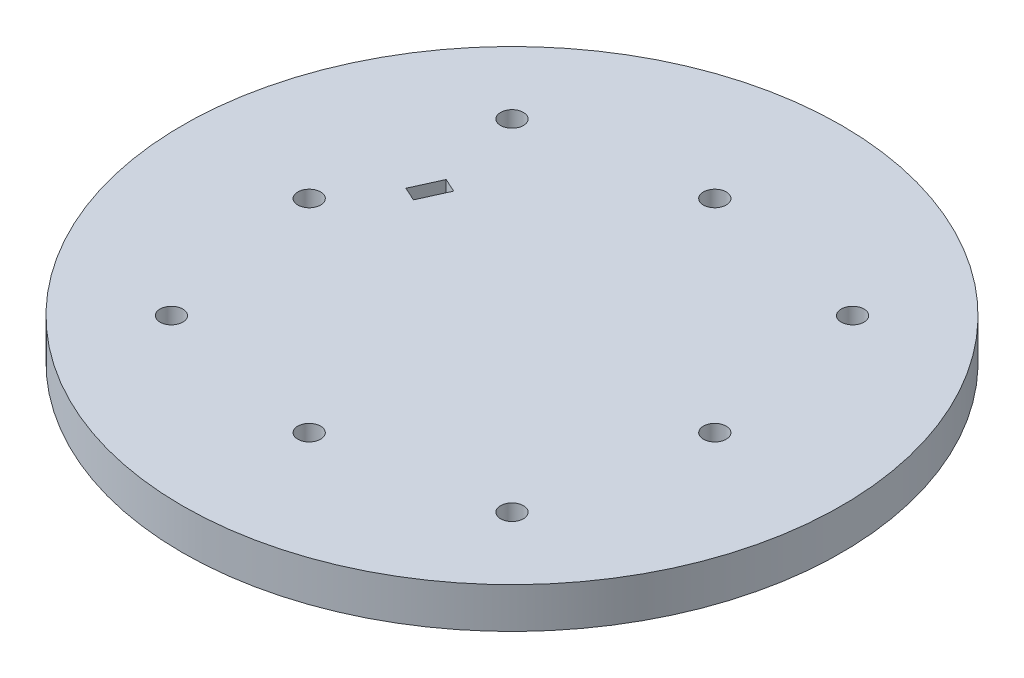
SolidWorks part; units mm, degrees
material "6061-T6 (SS)"
ref_plane "Front Plane" through (0, 0, 0) normal (0, 0, 1) x (1, 0, 0)
ref_plane "Top Plane" through (0, 0, 0) normal (0, 1, 0) x (1, 0, 0)
ref_plane "Right Plane" through (0, 0, 0) normal (1, 0, 0) x (0, 0, -1)
sketch "Sketch2" plane through (0, 0, 0) normal (0, 1, 0) x (1, 0, 0)
  circle A0 centre (0, 0) radius 65
  dimension "D1" = 130
extrude "Boss-Extrude1" add sketch "Sketch2" along normal blind 8
sketch "Sketch3" plane through (0, 0, 0) normal (0, -1, 0) x (1, 0, 0)
  circle A0 centre (0, 0) radius 21
  dimension "D1" = 42
extrude "Cut-Extrude1" cut sketch "Sketch3" against normal blind 4.5
sketch "Sketch4" plane through (0, 8, 0) normal (0, 1, 0) x (1, 0, 0)
  circle A0 centre (0, 0) radius 40 construction
  circle A1 centre (-40, 0) radius 2.25
  circle A2 centre (0, 40) radius 2.25
  circle A3 centre (0, 0) radius 40 construction
  circle A4 centre (40, 0) radius 2.25
  circle A5 centre (0, 0) radius 40 construction
  circle A6 centre (0, -40) radius 2.25
  circle A7 centre (0, 0) radius 40 construction
  point P17 (0, 0)
  dimension "D1" = 80
  dimension "D2" = 4.5
  dimension "D3" = 4
extrude "Cut-Extrude2" cut sketch "Sketch4" against normal through all
sketch "Sketch5" plane through (0, 8, 0) normal (0, 1, 0) x (1, 0, 0)
  line L0 (0, 40) -> (-40, 0) construction
  line L1 (-20, 20) -> (-33.5876, 33.5876) construction
  line L2 (-33.5876, 33.5876) -> (33.5876, -33.5876) construction
  line L3 (0, 0) -> (-33.5876, -33.5876) construction
  line L4 (-33.5876, -33.5876) -> (33.5876, 33.5876) construction
  circle A0 centre (0, 0) radius 47.5 construction
  circle A1 centre (-33.5876, 33.5876) radius 2.25
  circle A2 centre (33.5876, 33.5876) radius 2.25
  circle A3 centre (0, 0) radius 47.5 construction
  circle A4 centre (33.5876, -33.5876) radius 2.25
  circle A5 centre (0, 0) radius 47.5 construction
  circle A6 centre (-33.5876, -33.5876) radius 2.25
  circle A7 centre (0, 0) radius 47.5 construction
  point P25 (0, 0)
  dimension "D2" = 4.5
  dimension "D3" = 4
  dimension "D1" = 95
extrude "Cut-Extrude3" cut sketch "Sketch5" against normal through all
sketch "Sketch6" plane through (0, 0, 0) normal (0, -1, 0) x (1, 0, 0)
  line L0 (0, 0) -> (-68.3319, -30.9152) construction
  line L1 (-29.4805, -10.045) -> (-27.0073, -15.5116)
  line L6 (-27.0073, -15.5116) -> (-16.0741, -10.5651)
  line L7 (-16.0741, -10.5651) -> (-18.5474, -5.0986)
  line L8 (-18.5474, -5.0986) -> (-29.4805, -10.045)
  line L9 (-20.3695, -5.923) -> (-17.8963, -11.3895) construction
  circle A1 centre (0, 0) radius 21 construction
  point P9 (-17.3108, -7.8318)
  dimension "D1" = 6
  dimension "D2" = 4
  dimension "D3" = 10
extrude "path_trench" cut sketch "Sketch6" against normal blind 2
sketch "Sketch7" plane through (0, 0, 0) normal (0, -1, 0) x (1, 0, 0)
  line L5 (-29.4805, -10.045) -> (-32.2137, -11.2816)
  line L6 (-32.2137, -11.2816) -> (-29.7405, -16.7482)
  line L7 (-29.7405, -16.7482) -> (-27.0073, -15.5116)
  line L8 (-27.0073, -15.5116) -> (-17.7001, -11.3007) construction
  line L9 (-20.1733, -5.8342) -> (-29.4805, -10.045) construction
  line L10 (-29.4805, -10.045) -> (-27.0073, -15.5116)
  dimension "D1" = 3
sketch "CDG" plane through (0, 0, 0) normal (0, -1, 0) x (1, 0, 0)
  circle A0 centre (0, 0) radius 27 construction
  circle A1 centre (-27, 0) radius 1.7
  circle A2 centre (13.5, 23.3827) radius 1.7
  circle A3 centre (0, 0) radius 27 construction
  circle A4 centre (13.5, -23.3827) radius 1.7
  circle A5 centre (0, 0) radius 27 construction
  point P14 (0, 0)
  dimension "D1" = 54
  dimension "D3" = 3.4
  dimension "D2" = 3
extrude "CDG_CUT" cut sketch "CDG" against normal blind 6
extrude "Cut-Extrude4" cut sketch "Sketch7" against normal through all
sketch "Sketch8" plane through (0, 8, 0) normal (0, 1, 0) x (1, 0, 0)
  line L0 (-33.5876, 33.5876) -> (33.5876, 33.5876) construction
  line L1 (0, 33.5876) -> (0, -65) construction
  circle A0 centre (0, 0) radius 65 construction
equation "\"D1@Sketch2\"=\"CTRL_DiskOD\""
equation "\"D1@Boss-Extrude1\"=\"CTRL_DiskThk\""
equation "\"D1@Sketch3\"=\"ENCCAV_Dia\""
equation "\"D1@Cut-Extrude1\"=\"ENCCAV_Depth\""
equation "\"D1@Sketch4\"=\"CTRL_MainTowerDiskHoleBCD\""
equation "\"D2@Sketch4\"=\"CTRL_MainTowerHoleClearDia\""
equation "\"D1@Sketch5\"=\"UTR_BCD\""
equation "\"D2@Sketch5\"=\"CTRL_MainTowerHoleClearDia\""
equation "\"____ GENERATED PART EXPORTS ____\" = 0"
equation "\"SYS_VersionTag\" = 2"
equation "\"CTRL_DiskOD\" = 130mm"
equation "\"CTRL_DiskThk\" = 8mm"
equation "\"CTRL_ProtectedNoThroughDia\" = 52mm"
equation "\"ENCCAV_Dia\" = 42mm"
equation "\"ENCCAV_Depth\" = 4.5mm"
equation "\"CTRL_MainTowerDiskHoleBCD\" = 80mm"
equation "\"CTRL_MainTowerHoleClearDia\" = 4.5mm"
equation "\"CTRL_MainTowerHoleCountPerDeck\" = 4"
equation "\"CTRL_MainTowerOD\" = 8mm"
equation "\"UTR_BCD\" = 95mm"
equation "\"UTR_Count\" = 4"
equation "\"ENCCAV_TrenchWidth\" = 6mm"
equation "\"ENCCAV_TrenchDepth\" = 2mm"
equation "\"ENCCAV_TrenchExitSectorDeg\" = 225"
equation "\"CDG_ID\" = 42.5mm"
equation "\"CDG_WallThk\" = 2mm"
equation "\"CDG_OD\" = 46.5mm"
equation "\"CDG_SkirtLength\" = 30mm"
equation "\"CDG_FlangeThk\" = 3mm"
equation "\"CDG_MountBCDia\" = 54mm"
equation "\"CDG_MountClearDia\" = 3.4mm"
equation "\"CDG_MountCount\" = 3"
equation "\"CDG_ServiceSlotWidth\" = 10mm"
equation "\"CDG_ServiceSlotHeight\" = 18mm"
equation "\"CDG_ServiceSlotSectorDeg\" = 225"
equation "\"D1@path_trench\" = \"ENCCAV_TrenchDepth\""
equation "\"D1@CDG\"=\"CDG_MountBCDia\""
equation "\"D3@CDG\"=\"CDG_MountClearDia\""
equation "\"D1@Sketch6\"=\"ENCCAV_TrenchWidth\""
